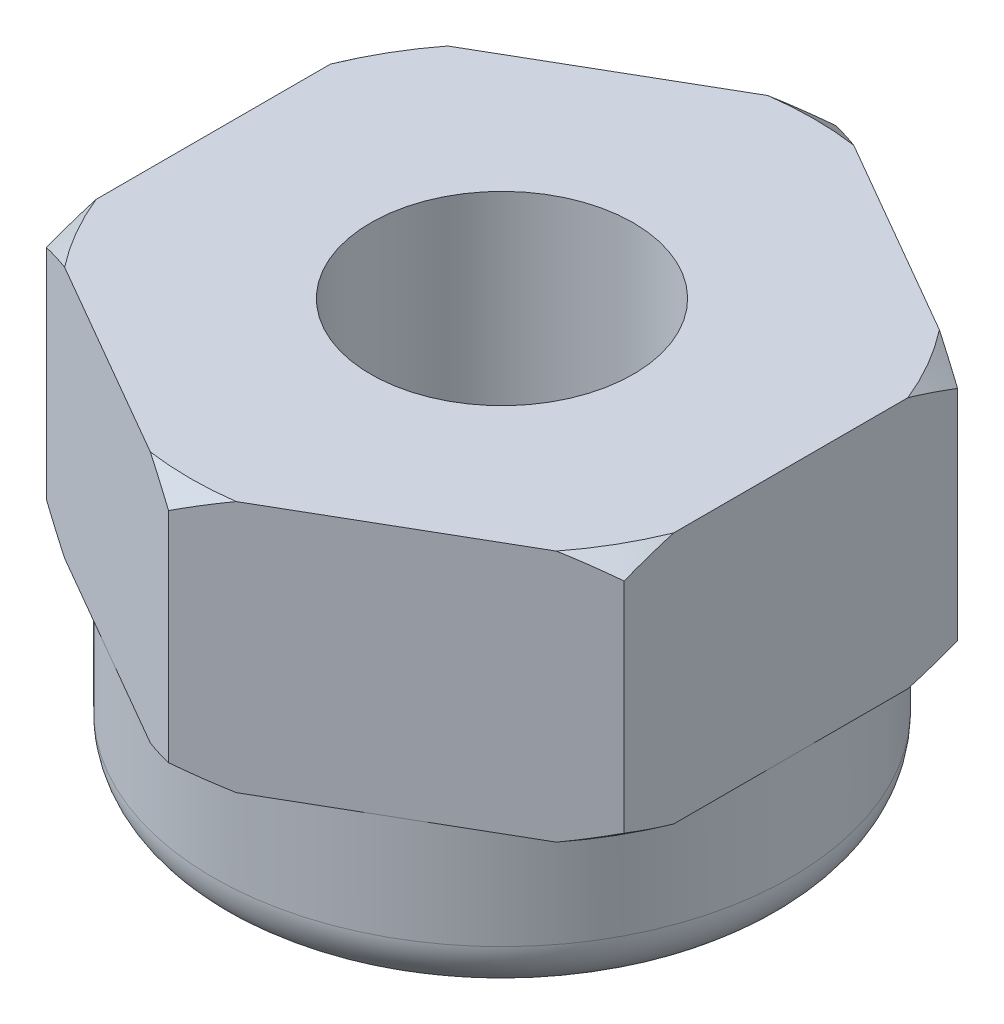
SolidWorks part; units mm, degrees
material "AISI 304"
ref_plane "前视基准面" through (0, 0, 0) normal (0, 0, 1) x (1, 0, 0)
ref_plane "上视基准面" through (0, 0, 0) normal (0, 1, 0) x (1, 0, 0)
ref_plane "右视基准面" through (0, 0, 0) normal (1, 0, 0) x (0, 0, -1)
sketch "草图1" plane through (0, 0, 0) normal (0, 1, 0) x (1, 0, 0)
  line L1 (0, 3.1754) -> (-2.75, 1.5877)
  line L2 (-2.75, 1.5877) -> (-2.75, -1.5877)
  line L3 (-2.75, -1.5877) -> (0, -3.1754)
  line L4 (0, -3.1754) -> (2.75, -1.5877)
  line L5 (2.75, -1.5877) -> (2.75, 1.5877)
  line L6 (2.75, 1.5877) -> (0, 3.1754)
  circle A0 centre (0, 0) radius 2.75 construction
  dimension "D1" = 5.5
extrude "凸台-拉伸1" add sketch "草图1" along normal blind 2.4
sketch "草图2" plane through (0, 0, 0) normal (0, -1, 0) x (1, 0, 0)
  circle A0 centre (0, 0) radius 2.75
extrude "凸台-拉伸2" add sketch "草图2" along normal blind 1.5
fillet "圆角1" radius 0.5 1 edges at (0, -1.5, -2.75)
hole_wizard "M3 螺纹孔1" positions "草图4" profile "草图5" tap size "M3" standard "GB" end condition through all
sketch "草图4" plane through (0, -1.5, 0) normal (0, -1, 0) x (-1, 0, 0)
  point P0 (0, 0)
sketch "草图5" plane through (0, -1.5, 0) normal (1, 0, 0) x (0, 0, -1)
  line L0 (0, 0) -> (0, 3.9)
  line L1 (0, 3.9) -> (1.25, 3.9)
  line L2 (1.25, 3.9) -> (1.25, 0)
  line L5 (1.25, 0) -> (0, 0)
  line L11 (0, -6.35) -> (0, 107.95) construction
  dimension "通孔螺纹孔钻头直径" = 2.5
  dimension "通孔螺纹孔钻头深度" = 3.9
cosmetic thread "孔螺蚊线1" parameters "D2"=3
sketch "草图6" plane through (0, 0, 0) normal (0, 0, 1) x (1, 0, 0)
  line L0 (-2.75, 2.1904) -> (-2.4135, 2.4)
  line L1 (-2.75, 2.4) -> (-2.75, 0) construction
  line L2 (-2.75, 2.4) -> (0, 2.4) construction
  line L3 (-2.4135, 2.4) -> (-2.75, 2.4)
  line L4 (-2.75, 2.4) -> (-2.75, 2.1904)
  line L5 (0, 0) -> (0, 3.5219) construction
sketch "草图7" plane through (0, 0, 0) normal (1, 0, 0) x (0, 0, -1)
  line L0 (-3.2713, 2.1655) -> (-2.9674, 2.4)
  line L1 (-3.1754, 2.4) -> (-1.5877, 2.4) construction
  line L2 (-2.9674, 2.4) -> (-3.3346, 2.4)
  line L3 (-3.3346, 2.4) -> (-3.2713, 2.1655)
  line L4 (0, 0) -> (0, 3.8391) construction
  line L8 (-3.3346, 0) -> (-3.2713, 0.2345)
  line L9 (-2.9674, 0) -> (-3.3346, 0)
  line L10 (-3.2713, 0.2345) -> (-2.9674, 0)
revolve "切除-旋转2" cut sketch "草图7" angle 360 about L4
